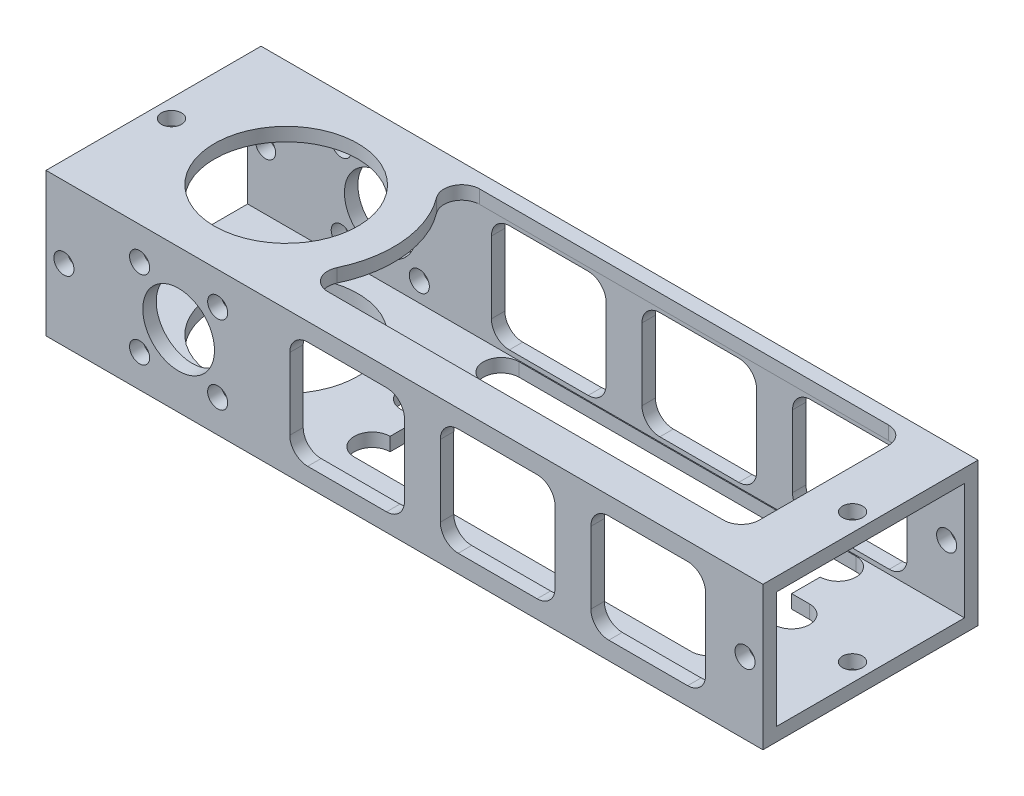
SolidWorks part; units mm, degrees
material "6061 Alloy"
ref_plane "Front Plane" through (0, 0, 0) normal (0, 0, 1) x (1, 0, 0)
ref_plane "Top Plane" through (0, 0, 0) normal (0, 1, 0) x (1, 0, 0)
ref_plane "Right Plane" through (0, 0, 0) normal (1, 0, 0) x (0, 0, -1)
sketch "Sketch1" plane through (0, 0, 0) normal (1, 0, 0) x (0, 0, -1)
  line L0 (2.3813, 23.0187) -> (35.7188, 23.0187)
  line L1 (0, 0) -> (38.1, 0)
  line L2 (0, 0) -> (0, 25.4)
  line L3 (0, 25.4) -> (38.1, 25.4)
  line L4 (38.1, 0) -> (38.1, 25.4)
  line L5 (35.7188, 2.3813) -> (35.7188, 23.0187)
  line L6 (2.3813, 2.3813) -> (35.7188, 2.3813)
  line L7 (2.3813, 2.3813) -> (2.3813, 23.0187)
  dimension "D1" = 38.1
  dimension "D2" = 25.4
  dimension "D3" = 2.3813
extrude "Boss-Extrude1" add sketch "Sketch1" along normal blind 127
sketch "Sketch2" plane through (0, 25.4, 0) normal (0, 1, 0) x (1, 0, 0)
  line L0 (0, 19.05) -> (23.495, 19.05) construction
  line L1 (0, 38.1) -> (0, 0) construction
  circle A0 centre (23.495, 19.05) radius 12.7
  dimension "D2" = 25.4
  dimension "D1" = 23.495
extrude "Cut-Extrude1" cut sketch "Sketch2" against normal through all
sketch "Sketch3" plane through (0, 0, 0) normal (0, 0, 1) x (1, 0, 0)
  line L0 (0, 12.7) -> (23.495, 12.7) construction
  line L1 (0, 25.4) -> (0, 0) construction
  line L2 (0, 25.4) -> (23.495, 25.4) construction
  line L3 (63.5, 22.225) -> (69.85, 22.225) construction
  line L4 (16.5802, 5.7852) -> (30.4098, 5.7852) construction
  line L5 (16.5802, 5.7852) -> (16.5802, 19.6148) construction
  line L6 (16.5802, 19.6148) -> (30.4098, 19.6148) construction
  line L7 (30.4098, 5.7852) -> (30.4098, 19.6148) construction
  line L8 (16.5802, 5.7852) -> (30.4098, 19.6148) construction
  line L9 (16.5802, 19.6148) -> (30.4098, 5.7852) construction
  line L10 (46.355, 22.225) -> (60.325, 22.225)
  line L11 (43.18, 19.05) -> (43.18, 6.35)
  line L12 (46.355, 3.175) -> (60.325, 3.175)
  line L13 (63.5, 19.05) -> (63.5, 6.35)
  line L14 (73.025, 22.225) -> (86.995, 22.225)
  line L15 (69.85, 19.05) -> (69.85, 6.35)
  line L16 (73.025, 3.175) -> (86.995, 3.175)
  line L17 (90.17, 19.05) -> (90.17, 6.35)
  line L18 (99.695, 22.225) -> (113.665, 22.225)
  line L19 (96.52, 19.05) -> (96.52, 6.35)
  line L20 (99.695, 3.175) -> (113.665, 3.175)
  line L21 (116.84, 19.05) -> (116.84, 6.35)
  line L22 (90.17, 22.225) -> (96.52, 22.225) construction
  line L23 (127, 12.7) -> (116.84, 12.7) construction
  line L24 (127, 25.4) -> (127, 0) construction
  circle A0 centre (23.495, 12.7) radius 6.35
  circle A1 centre (16.5802, 19.6148) radius 1.778
  circle A2 centre (16.5802, 5.7852) radius 1.778
  circle A3 centre (30.4098, 5.7852) radius 1.778
  circle A4 centre (30.4098, 19.6148) radius 1.778
  arc A5 (113.665, 22.225) -> (116.84, 19.05) centre (113.665, 19.05) cw
  arc A6 (113.665, 3.175) -> (116.84, 6.35) centre (113.665, 6.35) ccw
  arc A7 (96.52, 6.35) -> (99.695, 3.175) centre (99.695, 6.35) ccw
  arc A8 (99.695, 22.225) -> (96.52, 19.05) centre (99.695, 19.05) ccw
  arc A9 (86.995, 22.225) -> (90.17, 19.05) centre (86.995, 19.05) cw
  arc A10 (86.995, 3.175) -> (90.17, 6.35) centre (86.995, 6.35) ccw
  arc A11 (69.85, 6.35) -> (73.025, 3.175) centre (73.025, 6.35) ccw
  arc A12 (73.025, 22.225) -> (69.85, 19.05) centre (73.025, 19.05) ccw
  arc A13 (60.325, 22.225) -> (63.5, 19.05) centre (60.325, 19.05) cw
  arc A14 (60.325, 3.175) -> (63.5, 6.35) centre (60.325, 6.35) ccw
  arc A15 (43.18, 6.35) -> (46.355, 3.175) centre (46.355, 6.35) ccw
  arc A16 (46.355, 22.225) -> (43.18, 19.05) centre (46.355, 19.05) ccw
  point P33 (116.84, 22.225)
  point P36 (116.84, 3.175)
  dimension "D1" = 12.7
  dimension "D3" = 3.556
  dimension "D8" = 3.175
  dimension "D2" = 19.558
  dimension "D4" = 20.32
  dimension "D5" = 19.05
  dimension "D6" = 6.35
  dimension "D7" = 10.16
extrude "Cut-Extrude2" cut sketch "Sketch3" against normal through all
sketch "Sketch4" plane through (0, 25.4, 0) normal (0, 1, 0) x (1, 0, 0)
  line L0 (43.5755, 6.35) -> (113.665, 6.35)
  line L1 (116.84, 9.525) -> (116.84, 32.385)
  line L2 (113.665, 35.56) -> (41.275, 35.56)
  line L3 (116.84, 19.05) -> (127, 19.05) construction
  line L4 (127, 38.1) -> (127, 0) construction
  line L5 (127, 0) -> (116.84, 0) construction
  line L6 (127, 38.1) -> (0, 38.1) construction
  line L7 (127, 0) -> (0, 0) construction
  line L8 (78.6202, 6.35) -> (78.6202, 35.56) construction
  arc A0 (40.7068, 10.8857) -> (38.735, 30.48) centre (23.495, 19.05) ccw
  circle A1 centre (23.495, 19.05) radius 12.7 construction
  arc A2 (113.665, 6.35) -> (116.84, 9.525) centre (113.665, 9.525) ccw
  arc A3 (116.84, 32.385) -> (113.665, 35.56) centre (113.665, 32.385) ccw
  arc A4 (38.735, 30.48) -> (41.275, 35.56) centre (41.275, 32.385) cw
  arc A5 (40.7068, 10.8857) -> (43.5755, 6.35) centre (43.5755, 9.525) ccw
  dimension "D3" = 6.35
  dimension "D4" = 3.175
  dimension "D1" = 2.54
  dimension "D2" = 6.35
extrude "Cut-Extrude3" cut sketch "Sketch4" against normal up to next
hole_wizard "#4 (0.209) Diameter Hole1" positions "3DSketch1" profile "Sketch5" hole size "#4" standard "ANSI Inch" end condition up to next
sketch3d "3DSketch1"
  line L0 (127, 25.4, -19.05) -> (123.825, 25.4, -19.05) construction
  line L1 (127, 25.4, -38.1) -> (127, 25.4, 0) construction
  line L6 (127, 12.7, 0) -> (123.825, 12.7, 0) construction
  line L7 (127, 25.4, 0) -> (127, 0, 0) construction
  line L13 (0, 25.4, -19.05) -> (3.175, 25.4, -19.05) construction
  line L14 (0, 25.4, -38.1) -> (0, 25.4, 0) construction
  line L17 (0, 12.7, 0) -> (3.175, 12.7, 0) construction
  line L18 (0, 25.4, 0) -> (0, 0, 0) construction
  point P13 (123.825, 12.7, 0)
  point P24 (3.175, 25.4, -19.05)
  point P30 (3.175, 12.7, 0)
  point P48 (3.175, 25.4, -19.05)
  point P67 (3.175, 25.4, -19.05)
  point P69 (3.175, 12.7, 0)
  point P77 (123.825, 25.4, -19.05)
  point P79 (123.825, 12.7, 0)
  point P81 (123.825, 0, -19.05)
  point P83 (123.825, 12.7, -38.1)
  point P90 (3.175, 12.7, -38.1)
  point P92 (3.175, 0, -19.05)
  dimension "D1" = 3.175
sketch "Sketch5" plane through (3.175, 25.4, -19.05) normal (1, 0, 0) x (0, 0, 1)
  line L0 (0, 0) -> (0, 2.3822)
  line L1 (0, 2.3822) -> (1.778, 2.3822)
  line L2 (1.778, 2.3822) -> (1.778, 0)
  line L5 (1.778, 0) -> (0, 0)
  line L11 (0, -6.35) -> (0, 107.95) construction
  dimension "Thru Hole Dia." = 3.556
  dimension "Thru Hole Depth" = 2.3823
sketch "Sketch6" plane through (0, 0, 0) normal (0, -1, 0) x (1, 0, 0)
  line L0 (48.26, -35.56) -> (107.95, -35.56)
  line L1 (48.26, -6.35) -> (107.95, -6.35)
  line L2 (78.6202, -6.35) -> (78.6202, -35.56) construction
  line L3 (113.665, -35.56) -> (41.275, -35.56) construction
  line L4 (127, 0) -> (127, -38.1) construction
  line L5 (48.26, -6.35) -> (48.26, -35.56) construction
  line L6 (107.95, -6.35) -> (107.95, -35.56) construction
  line L8 (107.95, -12.7) -> (107.95, -17.78)
  line L9 (107.95, -17.78) -> (111.125, -17.78)
  line L10 (107.95, -29.21) -> (107.95, -24.13)
  line L11 (107.95, -24.13) -> (111.125, -24.13)
  line L12 (48.26, -29.21) -> (48.26, -24.13)
  line L13 (48.26, -12.7) -> (48.26, -17.78)
  line L14 (48.26, -17.78) -> (45.085, -17.78)
  line L15 (48.26, -24.13) -> (45.085, -24.13)
  arc A0 (107.95, -6.35) -> (107.95, -12.7) centre (107.95, -9.525) cw
  arc A1 (107.95, -35.56) -> (107.95, -29.21) centre (107.95, -32.385) ccw
  arc A2 (48.26, -35.56) -> (48.26, -29.21) centre (48.26, -32.385) cw
  arc A3 (48.26, -6.35) -> (48.26, -12.7) centre (48.26, -9.525) ccw
  arc A5 (111.125, -17.78) -> (111.125, -24.13) centre (111.125, -20.955) cw
  arc A6 (45.085, -17.78) -> (45.085, -24.13) centre (45.085, -20.955) ccw
  dimension "D1" = 59.69
  dimension "D2" = 3.175
  dimension "D3" = 3.175
  dimension "D4" = 19.05
extrude "Cut-Extrude4" cut sketch "Sketch6" against normal up to next
